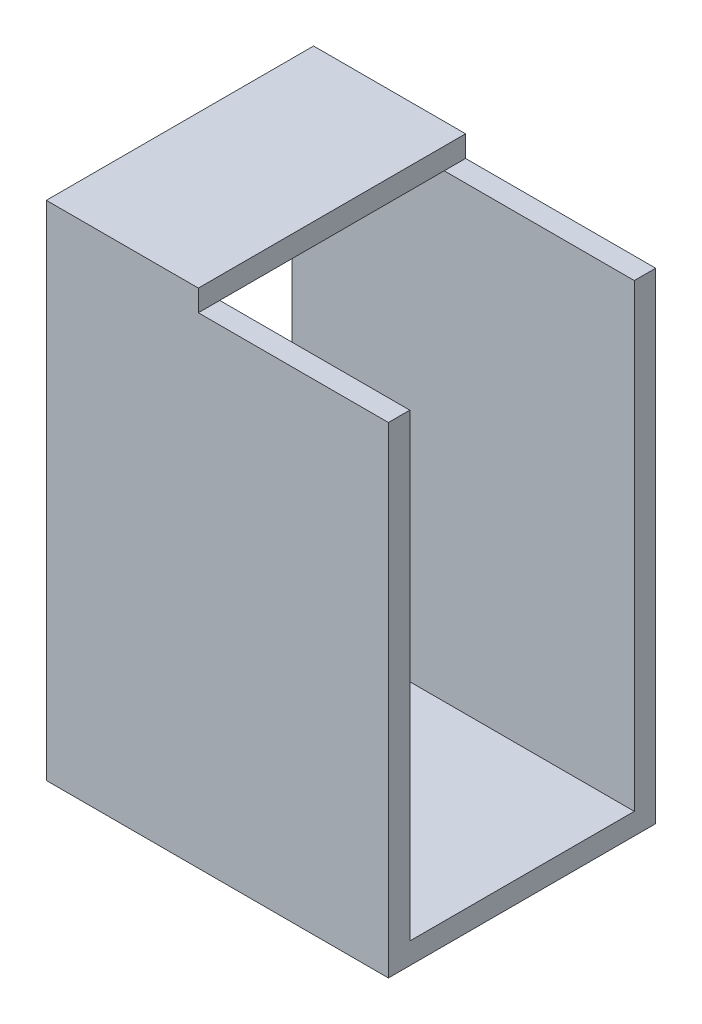
SolidWorks part; units mm, degrees
ref_plane "Front Plane" through (0, 0, 0) normal (0, 0, 1) x (1, 0, 0)
ref_plane "Top Plane" through (0, 0, 0) normal (0, 1, 0) x (1, 0, 0)
ref_plane "Right Plane" through (0, 0, 0) normal (1, 0, 0) x (0, 0, -1)
sketch "Sketch1" plane through (0, 0, 0) normal (0, 0, 1) x (1, 0, 0)
  line L1 (0, 0) -> (160, 0)
  line L2 (0, 0) -> (0, 215)
  line L3 (0, 215) -> (160, 215)
  line L4 (160, 0) -> (160, 215)
  dimension "D1" = 160
  dimension "D2" = 215
extrude "Boss-Extrude1" add sketch "Sketch1" along normal blind 105
fillet "Fillet1" [suppressed] radius 20
shell "Shell2" thickness 10
sketch "Sketch3" [suppressed] plane through (0, 0, 0) normal (1, 0, 0) x (0, 0, -1)
  line L0 (0, 20) -> (0, 195) construction
  line L1 (-85, 0) -> (-20, 0) construction
  line L2 (-105, 20) -> (-105, 195) construction
  line L3 (-85, 215) -> (-20, 215) construction
  line L4 (0, 20) -> (0, 195) construction
  line L5 (-85, 0) -> (-20, 0) construction
  line L6 (-105, 20) -> (-105, 195) construction
  line L7 (-85, 215) -> (-20, 215) construction
  line L8 (-85, 218) -> (-20, 218)
  line L9 (3, 20) -> (3, 195)
  line L10 (-85, -3) -> (-20, -3)
  line L11 (-108, 20) -> (-108, 195)
  arc A0 (0, 195) -> (-20, 215) centre (-20, 195) ccw construction
  arc A1 (-20, 0) -> (0, 20) centre (-20, 20) ccw construction
  arc A2 (-105, 20) -> (-85, 0) centre (-85, 20) ccw construction
  arc A3 (-85, 215) -> (-105, 195) centre (-85, 195) ccw construction
  arc A4 (0, 195) -> (-20, 215) centre (-20, 195) ccw construction
  arc A5 (-20, 0) -> (0, 20) centre (-20, 20) ccw construction
  arc A6 (-105, 20) -> (-85, 0) centre (-85, 20) ccw construction
  arc A7 (-85, 215) -> (-105, 195) centre (-85, 195) ccw construction
  arc A8 (3, 195) -> (-20, 218) centre (-20, 195) ccw
  arc A9 (-20, -3) -> (3, 20) centre (-20, 20) ccw
  arc A10 (-108, 20) -> (-85, -3) centre (-85, 20) ccw
  arc A11 (-85, 218) -> (-108, 195) centre (-85, 195) ccw
  dimension "D1" = 3
extrude "Cut-Extrude1" [suppressed] cut sketch "Sketch3" along normal up to surface (150 mm away)
sketch "Sketch5" [suppressed] plane through (0, 0, -10) normal (0, 0, -1) x (-1, 0, 0)
  line L0 (0, 190) -> (-160, 190) construction
  line L1 (-150, 20) -> (-60, 20)
  line L2 (-150, 20) -> (-150, 190)
  line L3 (-150, 190) -> (-60, 190)
  line L4 (-60, 20) -> (-60, 190)
  line L5 (-150, 190) -> (-150, 20) construction
  dimension "D1" = 90
extrude "Cut-Extrude2" [suppressed] cut sketch "Sketch5" against normal blind 10
sketch "Sketch6" plane through (0, 225, 0) normal (0, -1, 0) x (1, 0, 0)
  line L1 (160, -10) -> (0, -10) construction
  line L2 (160, 115) -> (71.1, 115)
  line L3 (160, 115) -> (160, -10)
  line L4 (160, -10) -> (71.1, -10)
  line L5 (71.1, 115) -> (71.1, -10)
  dimension "D1" = 88.9
extrude "Cut-Extrude3" cut sketch "Sketch6" along normal up to surface (10 mm away) contours L4 L5 L2 L3 up to face at (80, 215, 52.5)
